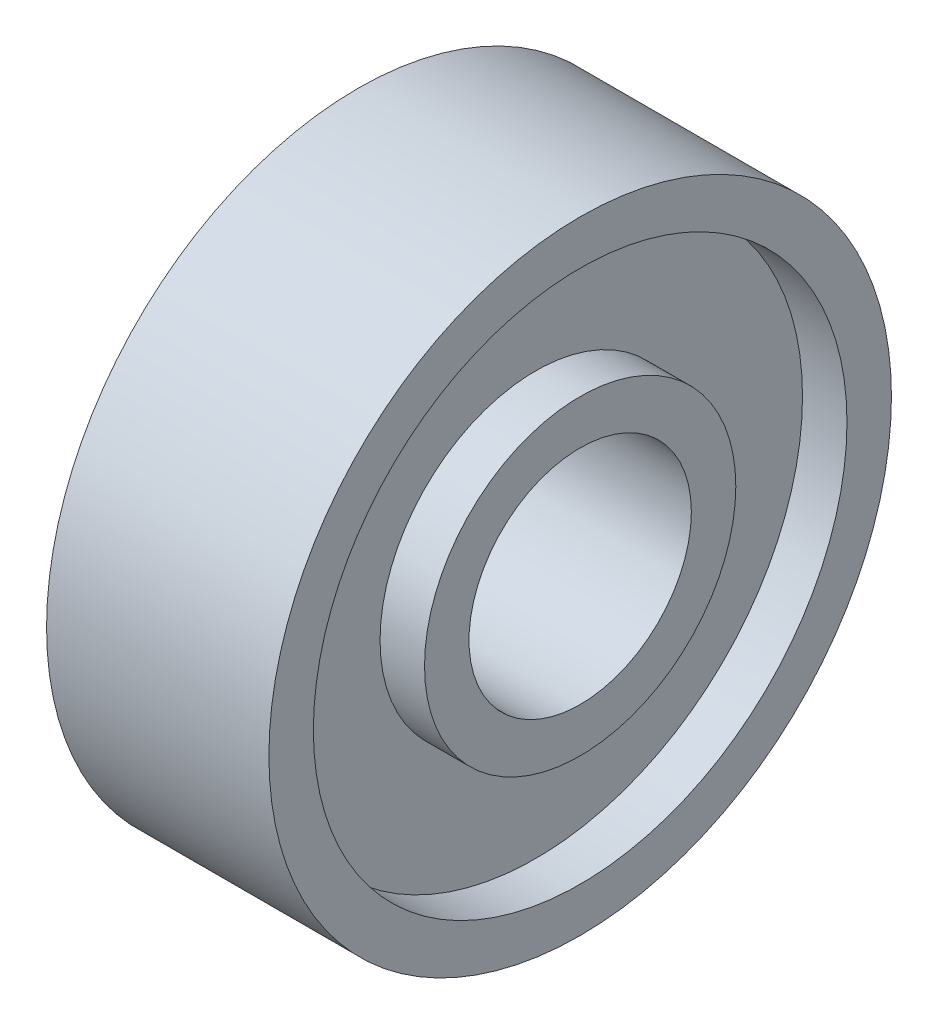
SolidWorks part; units mm, degrees
ref_plane "前视基准面" through (0, 0, 0) normal (1, 0, 0) x (0, 1, 0)
ref_plane "上视基准面" through (0, 0, 0) normal (0, 0, 1) x (0, 1, 0)
ref_plane "右视基准面" through (0, 0, 0) normal (0, 1, 0) x (-1, 0, 0)
other "Configuration Table"
sketch "草图1" plane through (0, 0, 0) normal (1, 0, 0) x (0, 1, 0)
  circle A0 centre (0, 0) radius 2.5
  circle A1 centre (0, 0) radius 7
  dimension "D1" = 14
  dimension "D2" = 5
extrude "凸台-拉伸1" add sketch "草图1" along normal mid plane 5
sketch "草图2" plane through (2.5, 0, 0) normal (1, 0, 0) x (0, 0, -1)
  circle A0 centre (0, 0) radius 3.5
  circle A1 centre (0, 0) radius 2.5 construction
  circle A2 centre (0, 0) radius 6
  circle A3 centre (0, 0) radius 7 construction
  dimension "D1" = 1
  dimension "D2" = 1
extrude "切除-拉伸1" cut sketch "草图2" against normal blind 1
sketch "草图3" plane through (-2.5, 0, 0) normal (-1, 0, 0) x (0, 0, 1)
  circle A0 centre (0, 0) radius 3.5
  circle A1 centre (0, 0) radius 4.5
  circle A2 centre (0, 0) radius 2.5 construction
  dimension "D1" = 1
  dimension "D2" = 1
extrude "切除-拉伸2" cut sketch "草图3" against normal blind 1
